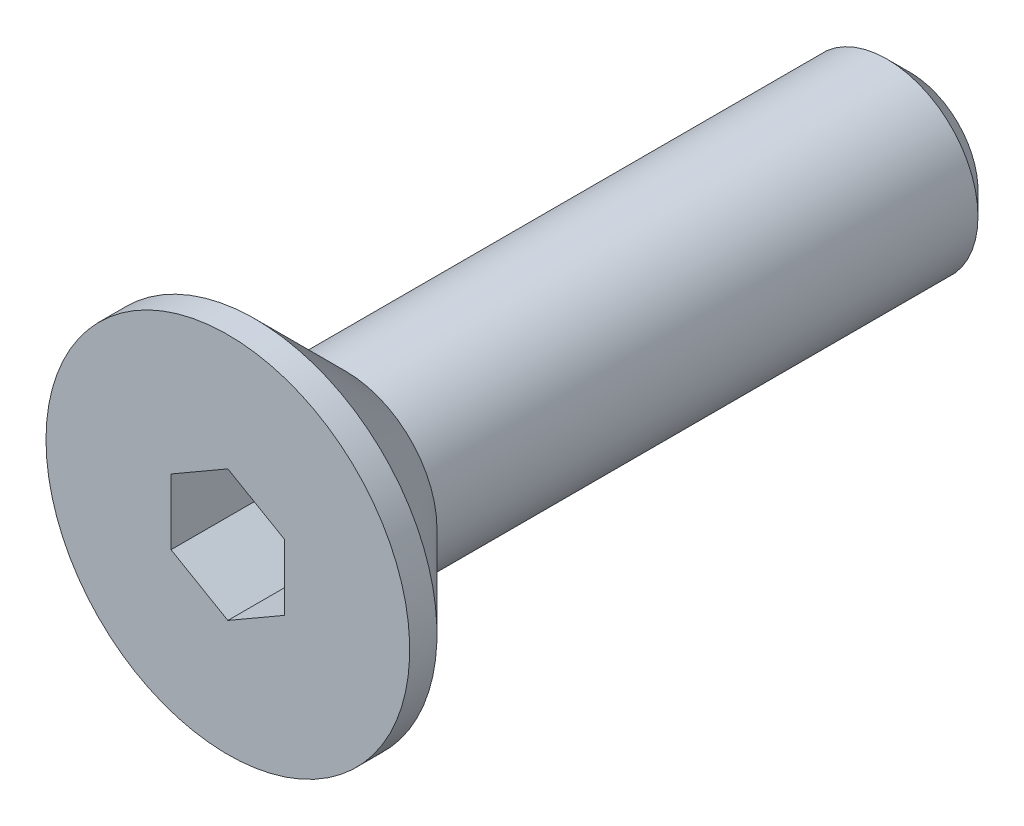
SolidWorks part; units mm, degrees
ref_plane "前视基准面" through (0, 0, 0) normal (0, 0, 1) x (1, 0, 0)
ref_plane "上视基准面" through (0, 0, 0) normal (0, 1, 0) x (1, 0, 0)
ref_plane "右视基准面" through (0, 0, 0) normal (1, 0, 0) x (0, 0, -1)
sketch "草图1" plane through (0, 0, 0) normal (1, 0, 0) x (0, 0, -1)
  line L0 (-7.5, 0) -> (-7.5, 4)
  line L1 (-7.5, 4) -> (-6.9, 4)
  line L2 (-6.9, 4) -> (-4.9, 2)
  line L3 (-4.9, 2) -> (7.5, 2)
  line L5 (7.5, 2) -> (7.5, 0)
  line L6 (7.5, 0) -> (-7.5, 0)
  dimension "D1" = 45
  dimension "D2" = 2
  dimension "D3" = 15
  dimension "D4" = 4
  dimension "D5" = 2.6
revolve "旋转1" add sketch "草图1" angle 360 about L6
chamfer "倒角1" distance 0.5 angle 45 1 edges at (-2, 0, -7.5)
sketch "草图2" plane through (0, 0, 7.5) normal (0, 0, 1) x (1, 0, 0)
  line L1 (0, 1.4434) -> (-1.25, 0.7217)
  line L2 (-1.25, 0.7217) -> (-1.25, -0.7217)
  line L3 (-1.25, -0.7217) -> (0, -1.4434)
  line L4 (0, -1.4434) -> (1.25, -0.7217)
  line L5 (1.25, -0.7217) -> (1.25, 0.7217)
  line L6 (1.25, 0.7217) -> (0, 1.4434)
  circle A0 centre (0, 0) radius 1.25 construction
  dimension "D1" = 2.5
extrude "切除-拉伸1" cut sketch "草图2" against normal blind 2.5
